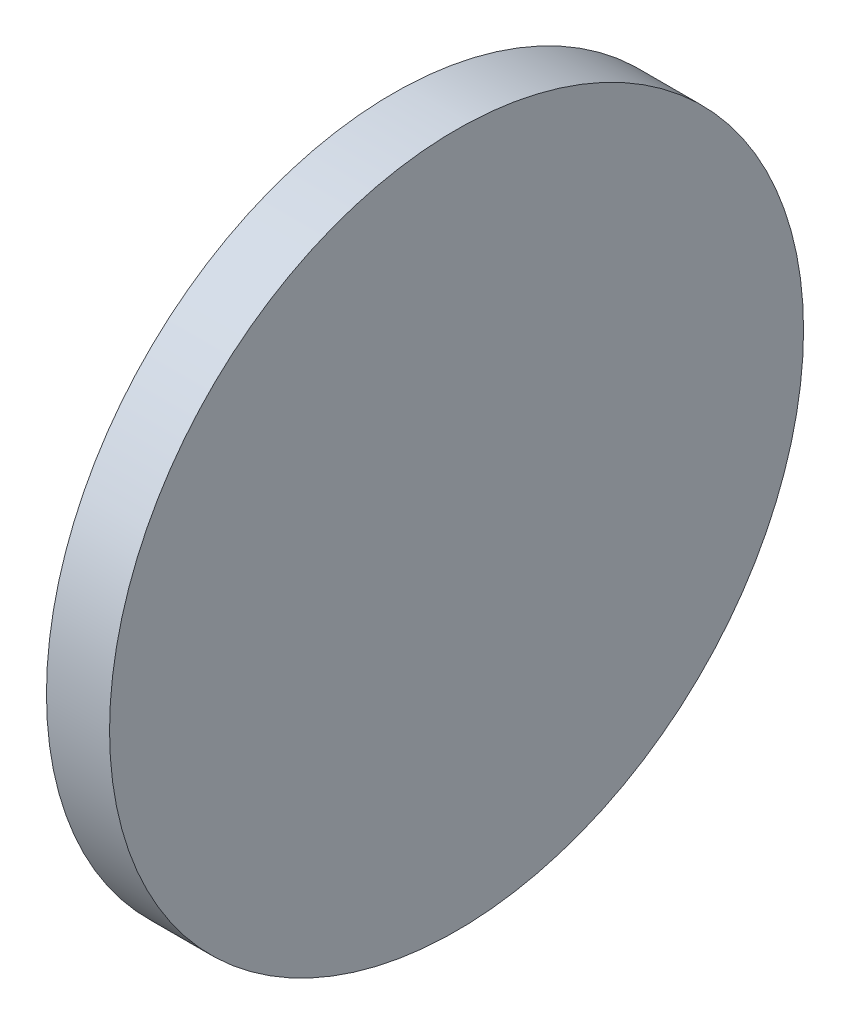
SolidWorks part; units mm, degrees
ref_plane "Front Plane" through (0, 0, 0) normal (0, 0, 1) x (1, 0, 0)
ref_plane "Top Plane" through (0, 0, 0) normal (0, 1, 0) x (1, 0, 0)
ref_plane "Right Plane" through (0, 0, 0) normal (1, 0, 0) x (0, 0, -1)
sketch "Sketch1" plane through (0, 0, 0) normal (1, 0, 0) x (0, 0, -1)
  circle A0 centre (0, 0) radius 11
  dimension "D1" = 22
extrude "Boss-Extrude1" add sketch "Sketch1" along normal blind 2
